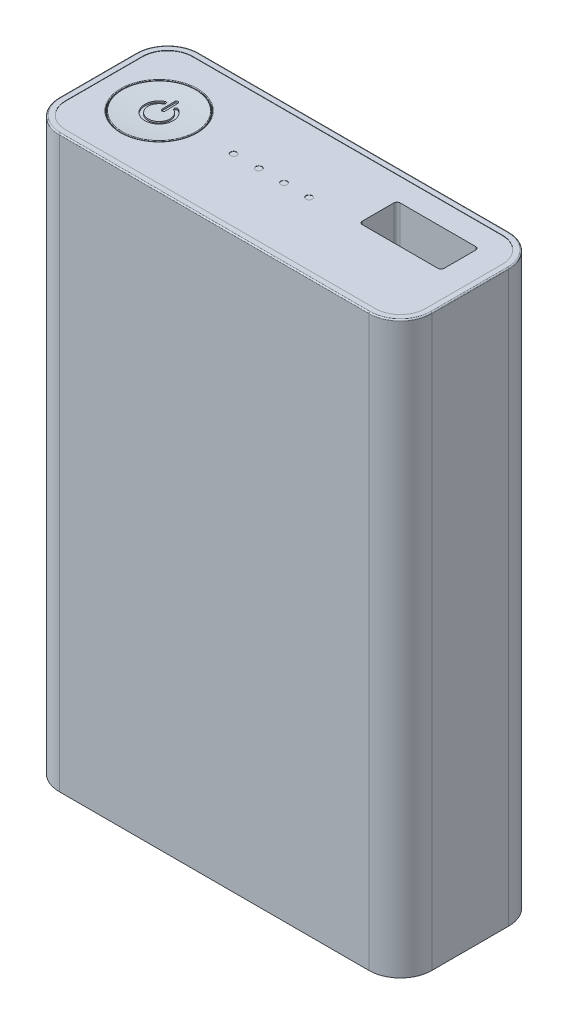
SolidWorks part; units mm, degrees
other "Camera1"
other "Camera2"
ref_plane "前基準面" through (0, 0, 0) normal (0, 0, 1) x (1, 0, 0)
ref_plane "上基準面" through (0, 0, 0) normal (0, 1, 0) x (1, 0, 0)
ref_plane "右基準面" through (0, 0, 0) normal (1, 0, 0) x (0, 0, -1)
sketch "Sketch1" plane through (0, 0, 0) normal (0, 1, 0) x (1, 0, 0)
  line L1 (-29.6, -11.1) -> (29.6, -11.1)
  line L2 (-29.6, -11.1) -> (-29.6, 11.1)
  line L3 (-29.6, 11.1) -> (29.6, 11.1)
  line L4 (29.6, -11.1) -> (29.6, 11.1)
  line L5 (-29.6, -11.1) -> (29.6, 11.1) construction
  line L6 (-29.6, 11.1) -> (29.6, -11.1) construction
  point P0 (0, 0)
  dimension "D1" = 59.2
  dimension "D2" = 22.2
extrude "Extrude1" add sketch "Sketch1" along normal blind 90.6
fillet "Fillet1" radius 5 4 edges at (-29.6, 45.3, 11.1) (-29.6, 45.3, -11.1) (29.6, 45.3, -11.1) (29.6, 45.3, 11.1)
sketch "Sketch2" plane through (0, 90.6, 0) normal (0, 1, 0) x (1, 0, 0)
  line L8 (-28.6, 6.1) -> (-28.6, -6.1)
  line L9 (-24.6, -10.1) -> (24.6, -10.1)
  line L10 (28.6, -6.1) -> (28.6, 6.1)
  line L11 (24.6, 10.1) -> (-24.6, 10.1)
  line L12 (-28.6, 6.1) -> (-28.6, -6.1)
  line L13 (-24.6, -10.1) -> (24.6, -10.1)
  line L14 (28.6, -6.1) -> (28.6, 6.1)
  line L15 (24.6, 10.1) -> (-24.6, 10.1)
  arc A8 (-28.6, -6.1) -> (-24.6, -10.1) centre (-24.6, -6.1) ccw
  arc A9 (24.6, -10.1) -> (28.6, -6.1) centre (24.6, -6.1) ccw
  arc A10 (28.6, 6.1) -> (24.6, 10.1) centre (24.6, 6.1) ccw
  arc A11 (-24.6, 10.1) -> (-28.6, 6.1) centre (-24.6, 6.1) ccw
  arc A12 (-28.6, -6.1) -> (-24.6, -10.1) centre (-24.6, -6.1) ccw
  arc A13 (24.6, -10.1) -> (28.6, -6.1) centre (24.6, -6.1) ccw
  arc A14 (28.6, 6.1) -> (24.6, 10.1) centre (24.6, 6.1) ccw
  arc A15 (-24.6, 10.1) -> (-28.6, 6.1) centre (-24.6, 6.1) ccw
  dimension "D1" = 1
extrude "Extrude2" cut sketch "Sketch2" against normal blind 0.05
sketch "Sketch3" plane through (0, 90.55, 0) normal (0, 1, 0) x (1, 0, 0)
  line L0 (0, 0) -> (-19.854, 0) construction
  circle A0 centre (-19.854, 0) radius 6
  dimension "D1" = 12
extrude "Extrude3" cut sketch "Sketch3" against normal blind 10
sketch "Sketch4" plane through (0, 80.55, 0) normal (0, 1, 0) x (1, 0, 0)
  circle A3 centre (-19.854, 0) radius 5.9
  dimension "D1" = 11.8
extrude "Extrude4" add sketch "Sketch4" along normal blind 10 separate body
sketch "Sketch5" plane through (0, 0, 0) normal (0, 0, 1) x (1, 0, 0)
  line L0 (-19.854, 90.2688) -> (-18.9091, 90.2688) construction
  line L3 (-19.854, 80.55) -> (-19.854, 91.5942) construction
  line L4 (-13.854, 80.55) -> (-25.854, 80.55) construction
  line L5 (-25.754, 90.55) -> (-19.854, 90.55)
  line L6 (-19.854, 90.55) -> (-19.854, 90.2688)
  arc A0 (-19.854, 90.2688) -> (-25.754, 90.55) centre (-19.854, 152.302) cw
revolve "Cut-Revolve1" cut sketch "Sketch5" angle 360 about L3
fillet "Fillet2" radius 0.1 1 edges at (-19.854, 90.55, -5.9)
fillet "Fillet3" radius 0.1 1 edges at (-19.854, 90.55, 6)
sketch "Sketch6" plane through (0, 90.55, 0) normal (0, 1, 0) x (1, 0, 0)
  line L0 (0, 0) -> (-8, 0) construction
  circle A0 centre (-8, 0) radius 0.5
  circle A1 centre (-4, 0) radius 0.5
  circle A2 centre (0, 0) radius 0.5
  circle A3 centre (4, 0) radius 0.5
  dimension "D1" = 1
  dimension "D3" = 8
  dimension "D2" = 4
extrude "Extrude5" cut sketch "Sketch6" against normal blind 0.05
sketch "Sketch7" plane through (0, 90.55, 0) normal (0, 1, 0) x (1, 0, 0)
  line L0 (-19.854, 0.719) -> (-19.854, 2.7239) construction
  line L1 (-20.114, 0.719) -> (-20.114, 2.7239)
  line L2 (-19.594, 0.719) -> (-19.594, 2.7239)
  arc A0 (-20.8108, 1.7563) -> (-18.9711, 1.7946) centre (-19.854, 0) ccw construction
  arc A1 (-20.9351, 1.9846) -> (-18.8564, 2.0279) centre (-19.854, 0) ccw
  arc A2 (-20.6864, 1.528) -> (-19.0859, 1.5613) centre (-19.854, 0) ccw
  arc A3 (-20.9351, 1.9846) -> (-20.6864, 1.528) centre (-20.8108, 1.7563) cw
  arc A4 (-18.8564, 2.0279) -> (-19.0859, 1.5613) centre (-18.9711, 1.7946) ccw
  arc A5 (-20.114, 0.719) -> (-19.594, 0.719) centre (-19.854, 0.719) ccw
  arc A6 (-19.594, 2.7239) -> (-20.114, 2.7239) centre (-19.854, 2.7239) ccw
  point P12 (-19.854, 1.7214)
  dimension "D3" = 2
  dimension "D4" = 0.52
  dimension "D5" = 2.0049
  dimension "D1" = 0.26
  dimension "D2" = 0.26
extrude "Extrude8" cut sketch "Sketch7" against normal blind 0.5
fillet "Fillet4" radius 0.2 8 edges at (-28.1355, 90.6, 9.6355) (-29.6, 90.6, 0) (-28.1355, 90.6, -9.6355) (0, 90.6, -11.1) (28.1355, 90.6, -9.6355) (29.6, 90.6, 0) (28.1355, 90.6, 9.6355) (0, 90.6, 11.1)
sketch "Sketch8" plane through (0, 90.55, 0) normal (0, 1, 0) x (1, 0, 0)
  line L1 (11.4869, 6.4643) -> (24.4869, 6.4643)
  line L2 (11.4869, 6.4643) -> (11.4869, 0.4643)
  line L3 (11.4869, 0.4643) -> (24.4869, 0.4643)
  line L4 (24.4869, 6.4643) -> (24.4869, 0.4643)
  dimension "D1" = 13
  dimension "D2" = 6
extrude "Extrude9" cut sketch "Sketch8" against normal blind 10
fillet "Fillet5" radius 0.5 4 edges at (11.4869, 85.55, -0.4643) (24.4869, 85.55, -0.4643) (11.4869, 85.55, -6.4643) (24.4869, 85.55, -6.4643)
